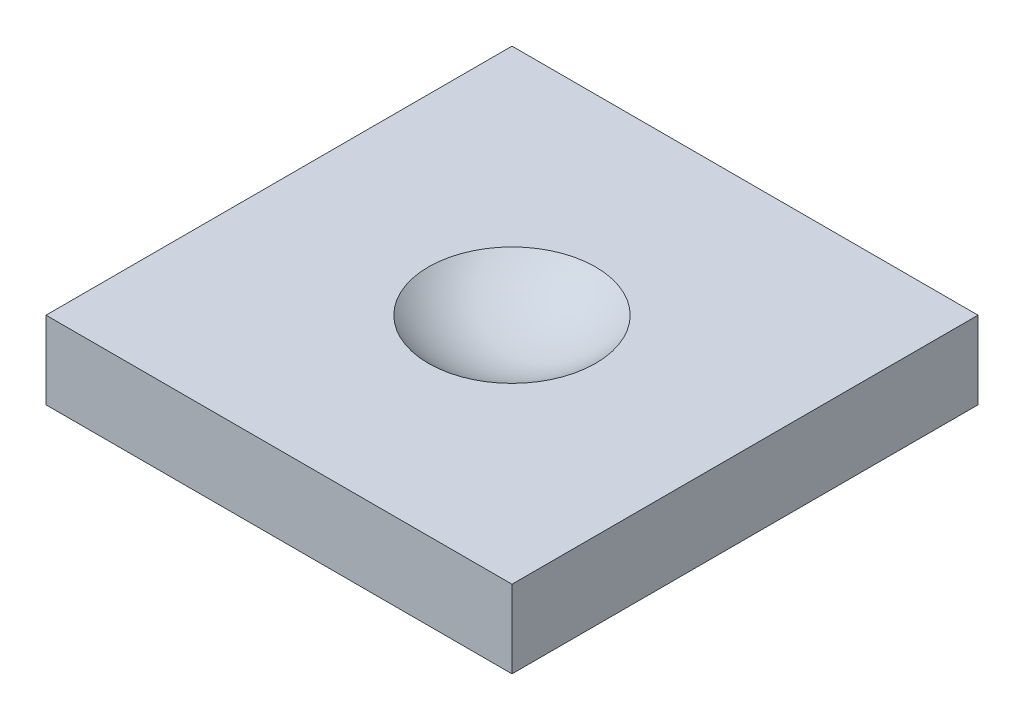
SolidWorks part; units mm, degrees
ref_plane "前视基准面" through (0, 0, 0) normal (0, 0, 1) x (1, 0, 0)
ref_plane "上视基准面" through (0, 0, 0) normal (0, 1, 0) x (1, 0, 0)
ref_plane "右视基准面" through (0, 0, 0) normal (1, 0, 0) x (0, 0, -1)
other "Configuration Table"
sketch "草图2" plane through (0, 0, 0) normal (0, 1, 0) x (1, 0, 0)
  line L1 (-60, -60) -> (60, -60)
  line L2 (-60, -60) -> (-60, 60)
  line L3 (-60, 60) -> (60, 60)
  line L4 (60, -60) -> (60, 60)
  line L5 (-60, -60) -> (60, 60) construction
  line L6 (-60, 60) -> (60, -60) construction
  point P0 (0, 0)
  point P6 (0, 0)
  dimension "D1" = 120
  dimension "D2" = 120
extrude "凸台-拉伸1" add sketch "草图2" along normal blind 20 contours L2 L3 L4 L1
sketch "草图3" plane through (0, 0, 0) normal (0, 0, 1) x (1, 0, 0)
  line L0 (0, 20) -> (0, 43) construction
  line L1 (-60, 20) -> (60, 20) construction
  line L2 (-31.5, 43) -> (0, 43)
  line L3 (0, 43) -> (31.5, 43)
  arc A0 (31.5, 43) -> (-31.5, 43) centre (0, 43) ccw
  dimension "D2" = 63
  dimension "D1" = 23
revolve "切除-旋转4" cut sketch "草图3" angle 360 about L2
sketch "草图4" plane through (0, 0, 0) normal (0, 1, 0) x (1, 0, 0)
  line L1 (49.925, 49.95) -> (-49.925, 49.95)
  line L2 (49.925, 49.95) -> (49.925, -49.95)
  line L3 (49.925, -49.95) -> (-49.925, -49.95)
  line L4 (-49.925, 49.95) -> (-49.925, -49.95)
  line L5 (49.925, 49.95) -> (-49.925, -49.95) construction
  line L6 (49.925, -49.95) -> (-49.925, 49.95) construction
  point P0 (0, 0)
  dimension "D1" = 99.9
  dimension "D2" = 99.85
extrude "切除-拉伸1" cut sketch "草图4" along normal blind 8 contours L2 L3 L4 L1
